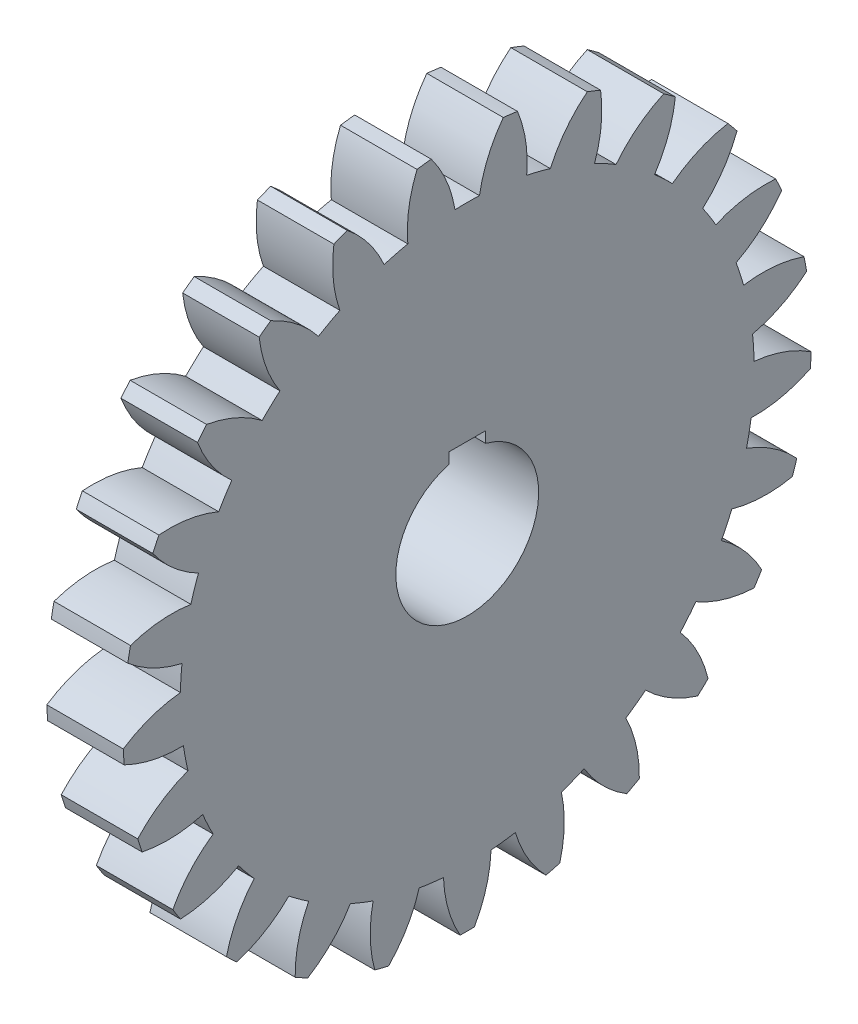
SolidWorks part; units mm, degrees
material "1023 Carbon Steel Sheet (SS)"
ref_plane "Plane1" through (0, 0, 0) normal (0, 0, 1) x (1, 0, 0)
ref_plane "Plane2" through (0, 0, 0) normal (0, 1, 0) x (1, 0, 0)
ref_plane "Plane3" through (0, 0, 0) normal (1, 0, 0) x (0, 0, -1)
sketch "HoldingSke" plane through (0, 0, 0) normal (0, 1, 0) x (1, 0, 0)
  line L0 (0, 0) -> (0.0363, -0.0169)
  line L1 (-15, 0) -> (100, 0) construction
  line L2 (0, 0) -> (-2.1039, 2.3779)
  line L3 (0, 0) -> (-11.863, 4.5341)
  line L4 (0, 0) -> (7.8269, 3.6497)
  line L5 (0, 0) -> (-93.6953, -34.9456)
  line L6 (0, 0) -> (-62.1722, -41.9478)
  line L7 (-2.1039, 2.3779) -> (19.4211, 100.0338)
  line L8 (-76.2, 54.61) -> (-67.8, 54.61)
  line L9 (-71.009, 38.7566) -> (-53.1078, 45.2721)
  line L10 (-76.2, 71.12) -> (104.1128, 71.12)
  line L11 (0, 0) -> (-75, 0)
  line L12 (-76.2, 101.6) -> (-75.26, 101.6)
  line L13 (24.9733, 27.94) -> (52.9518, 28.4284)
  line L14 (24.9733, 27.94) -> (24.9743, 27.94)
  line L15 (24.9733, 27.94) -> (100.4006, 29.5858)
  line L16 (-63.627, -25) -> (-12.827, -25)
  circle A0 centre (0, 0) radius 70
  circle A1 centre (0, 0) radius 175
  circle A2 centre (0, 0) radius 175
  circle A3 centre (0, 0) radius 70
  dimension "Pitch" = 0.04
  dimension "Thickness" = 75
  dimension "Ap" = 20
  dimension "H" = 19.05
  dimension "Pitch_radius" = 180.3128
  dimension "Width" = 75
  dimension "Backlash" = 0.94
  dimension "Addendum_fac" = 1
  dimension "Dedendum_fac" = 1.25
  dimension "Clearance_fac" = 0.25
  dimension "Dedendum_add" = 0.001
  dimension "Module" = 25
sketch "BasProSke" plane through (0, 0, 0) normal (0, 1, 0) x (1, 0, 0)
  line L0 (-10, 0) -> (60, 0) construction
  line L1 (0, 0) -> (0, 337.5)
  line L2 (0, 0) -> (75, 0)
  line L3 (75, 0) -> (75, 337.5)
  line L4 (75, 337.5) -> (0, 337.5)
  dimension "Thickness" = 75
revolve "Base-Revolve" add sketch "BasProSke" angle 360 about L0
sketch "TooCutSke" plane through (0, 0, 0) normal (1, 0, 0) x (0, 0, -1)
  line L1 (0, 0) -> (0, 107) construction
  line L2 (0, 0) -> (-21.2665, 311.7755) construction
  line L3 (0, 0) -> (-78.2035, 619.0448) construction
  line L4 (-21.2665, 311.7755) -> (-39.1018, 309.5224) construction
  arc A0 (11.9904, 280.9933) -> (-11.9904, 280.9933) centre (0, 0) ccw
  arc A1 (35.3567, 335.6684) -> (-35.3567, 335.6684) centre (0, 0) ccw
  circle A2 centre (0, 0) radius 312.5 construction
  circle A3 centre (0, 0) radius 293.6539 construction
  arc A4 (-11.9904, 280.9933) -> (-35.3567, 335.6684) centre (-135.3185, 260.6176) ccw
  arc A5 (35.3567, 335.6684) -> (11.9904, 280.9933) centre (135.3185, 260.6176) ccw
extrude "ToothCut" cut sketch "TooCutSke" along normal through all
fillet "Breaks" [suppressed] radius 0.5
fillet "RootFillets" [suppressed] radius 6.251
pattern_circular "TeethCuts" count 25 every 14.4 about axis through (-10, 0, 0) along (1, 0, 0) of "ToothCut", "RootFillets", "Breaks"
sketch "HubNeaOneSke" plane through (0, 0, 0) normal (-1, 0, 0) x (0, 0, 1)
  circle A0 centre (0, 0) radius 175
extrude "HubNearOne" add sketch "HubNeaOneSke" along normal blind 25.0001
sketch "HubNeaBotSke" plane through (0, 0, 0) normal (-1, 0, 0) x (0, 0, 1)
  circle A0 centre (0, 0) radius 175
extrude "HubNearBoth" [suppressed] add sketch "HubNeaBotSke" along normal blind 12.5
ref_plane "FarPln" through (75, 0, 0) normal (1, 0, 0) x (0, 0, -1)
sketch "HubFarSke" plane through (75, 0, 0) normal (1, 0, 0) x (0, 0, -1)
  circle A0 centre (0, 0) radius 175
extrude "HubFar" [suppressed] add sketch "HubFarSke" along normal blind 12.5
sketch "BorSke" plane through (0, 0, 0) normal (1, 0, 0) x (0, 0, -1)
  circle A0 centre (0, 0) radius 70
extrude "Bore" cut sketch "BorSke" along normal mid plane 200.0001
sketch "KeySke" plane through (0, 0, 0) normal (1, 0, 0) x (0, 0, -1)
  line L0 (-18, 0) -> (-18, 78.4)
  line L1 (-18, 78.4) -> (18, 78.4)
  line L2 (18, 78.4) -> (18, 0)
  line L3 (0, 0) -> (0, 34) construction
  line L4 (-18, 0) -> (18, 0)
extrude "Keyway" cut sketch "KeySke" along normal mid plane 200.0001
pattern_circular "Keyway2" [suppressed] count 2 every 90 about axis through (-10, 0, 0) along (1, 0, 0)
equation "' \"Module@HoldingSke\" = 6.35"
equation "' \"Num_teeth@HoldingSke\" = 12"
equation "' \"Ap@HoldingSke\" =  20"
equation "' \"Ap@HoldingSke\" = 20"
equation "' \"Width@HoldingSke\" = 0.5 * 25.4"
equation "' \"Hub_dia@HoldingSke\"= 1 * 25.4"
equation "' \"Hub_dia@HoldingSke\" = 1 * 25.4"
equation "' \"Overall_len@HoldingSke\" = 1.0 * 25.4"
equation "' \"Bore@HoldingSke\" = 0.75 * 25.4"
equation "' \"T_dim@HoldingSke\" = 0.1 * 25.4"
equation "' \"Width@KeySke\" = 0.25 * 25.4"
equation "' \"Show_teeth@HoldingSke\" = 13"
equation "' \"Backlash@HoldingSke\" = 0.009 * 25.4"
equation "' \"Addendum_fac@HoldingSke\" = 1.0"
equation "' \"Dedendum_fac@HoldingSke\" = 1.25"
equation "' \"Dedendum_add@HoldingSke\" = 0.00005 * 25.4"
equation "' \"Clearance_fac@HoldingSke\" = 0.25"
equation "\"Pitch@HoldingSke\" = 1 / \"Module@HoldingSke\""
equation "\"Overcut_dia@TooCutSke\" = (\"Num_teeth@HoldingSke\" + 2 * \"Addendum_fac@HoldingSke\") / \"Pitch@HoldingSke\" + 0.002 * 25.4"
equation "\"Pitch_dia@TooCutSke\" = \"Num_teeth@HoldingSke\" / \"Pitch@HoldingSke\""
equation "\"Base_dia@TooCutSke\" = \"Num_teeth@HoldingSke\" / \"Pitch@HoldingSke\" * cos((\"Ap@HoldingSke\"  * 3.14159265 / 180))"
equation "\"Root_dia@TooCutSke\" = (\"Num_teeth@HoldingSke\" + 2) / \"Pitch@HoldingSke\" - 2 * (\"Addendum_fac@HoldingSke\" + \"Dedendum_fac@HoldingSke\") / \"Pitch@HoldingSke\" - \"Dedendum_add@HoldingSke\" * 2"
equation "\"Half_ang@TooCutSke\" = 180 / \"Num_teeth@HoldingSke\""
equation "\"Half_CT@TooCutSke\" = \"Num_teeth@HoldingSke\" / \"Pitch@HoldingSke\" * sin((3.14159265 / 2 / \"Num_teeth@HoldingSke\")) / 2 - 7 * \"Backlash@HoldingSke\" / 4"
equation "\"Flank_rad@TooCutSke\" = \"Num_teeth@HoldingSke\" / \"Pitch@HoldingSke\" / 5"
equation "\"Radius@RootFillets\" = \"Clearance_fac@HoldingSke\" / \"Pitch@HoldingSke\" + \"Dedendum_add@HoldingSke\""
equation "\"Break_rad@Breaks\" = 0.02 / \"Pitch@HoldingSke\""
equation "\"Thickness@HoldingSke\" = \"Width@HoldingSke\""
equation "\"OAL@HoldingSke\" = \"Thickness@HoldingSke\""
equation "\"MHD@HoldingSke\" = (\"Num_teeth@HoldingSke\" + 2) / \"Pitch@HoldingSke\" - 2 * (\"Addendum_fac@HoldingSke\" + \"Dedendum_fac@HoldingSke\")  / \"Pitch@HoldingSke\" - \"Dedendum_add@HoldingSke\" * 2"
equation "\"MBD@HoldingSke\" = (\"Num_teeth@HoldingSke\" + 2) / \"Pitch@HoldingSke\" - 2 * (\"Addendum_fac@HoldingSke\" + \"Dedendum_fac@HoldingSke\")  / \"Pitch@HoldingSke\" - \"Dedendum_add@HoldingSke\" * 2 - 0.002 * 25.4"
equation "\"MHD@HoldingSke\" = ((sgn( \"MHD@HoldingSke\" - \"Hub_dia@HoldingSke\" )-1)*( \"MHD@HoldingSke\" - \"Hub_dia@HoldingSke\" ))/-2+ \"Hub_dia@HoldingSke\""
equation "\"MBD@HoldingSke\" = ((sgn( \"MBD@HoldingSke\" - \"Bore@HoldingSke\" )-1)*( \"MBD@HoldingSke\" - \"Bore@HoldingSke\" ))/-2+ \"Bore@HoldingSke\""
equation "\"OAL@HoldingSke\" = ((sgn( \"OAL@HoldingSke\" - \"Overall_len@HoldingSke\" )+1)*( \"OAL@HoldingSke\" - \"Overall_len@HoldingSke\" ))/2 + \"Overall_len@HoldingSke\" + 0.000002 * 25.4"
equation "\"Num_teeth@TeethCuts\" = int( \"Show_teeth@HoldingSke\" ) + 1"
equation "\"Num_teeth@TeethCuts\" = ((sgn( \"Num_teeth@TeethCuts\" - \"Num_teeth@HoldingSke\" )-1)*( \"Num_teeth@TeethCuts\" - \"Num_teeth@HoldingSke\" ))/-2+ \"Num_teeth@HoldingSke\""
equation "\"Num_teeth@TeethCuts\" = ((sgn( \"Num_teeth@TeethCuts\" - 2.0)+1)*( \"Num_teeth@TeethCuts\" - 2.0))/2 +2.0"
equation "\"Angle@TeethCuts\" = 360.0 / \"Num_teeth@HoldingSke\""
equation "\"Diameter@BasProSke\" = (\"Num_teeth@HoldingSke\" + 2 * \"Addendum_fac@HoldingSke\") / \"Pitch@HoldingSke\""
equation "\"Thickness@BasProSke\"  = \"Thickness@HoldingSke\""
equation "' \"Fillet_rad@BasProSke\" =  \"Thickness@HoldingSke\" * 0.05"
equation "' \"Fillet_rad@BasProSke\" = \"Thickness@HoldingSke\" * 0.05"
equation "\"MHD@HoldingSke\" = ((sgn( \"MHD@HoldingSke\" - \"Root_dia@TooCutSke\" )-1)*( \"MHD@HoldingSke\" - \"Root_dia@TooCutSke\" ))/-2+ \"Root_dia@TooCutSke\""
equation "\"Diameter@HubNeaOneSke\" = \"MHD@HoldingSke\""
equation "\"Length@HubNearOne\" = \"OAL@HoldingSke\" - \"Thickness@BasProSke\""
equation "\"Diameter@HubNeaBotSke\" = \"MHD@HoldingSke\""
equation "\"Length@HubNearBoth\" = ( \"OAL@HoldingSke\" - \"Thickness@BasProSke\" ) / 2.0"
equation "\"Thickness@FarPln\" = \"Thickness@BasProSke\""
equation "\"Diameter@HubFarSke\" = \"MHD@HoldingSke\""
equation "\"Length@HubFar\" = ( \"OAL@HoldingSke\" - \"Thickness@BasProSke\" ) / 2.0"
equation "\"Diameter@BorSke\" = \"MBD@HoldingSke\""
equation "\"D1@Bore\" = \"OAL@HoldingSke\" * 2.0"
equation "\"D1@Keyway\" = \"OAL@HoldingSke\" * 2.0"
equation "\"Offset@KeySke\" = \"T_dim@HoldingSke\" + \"MBD@HoldingSke\" / 2.0"
